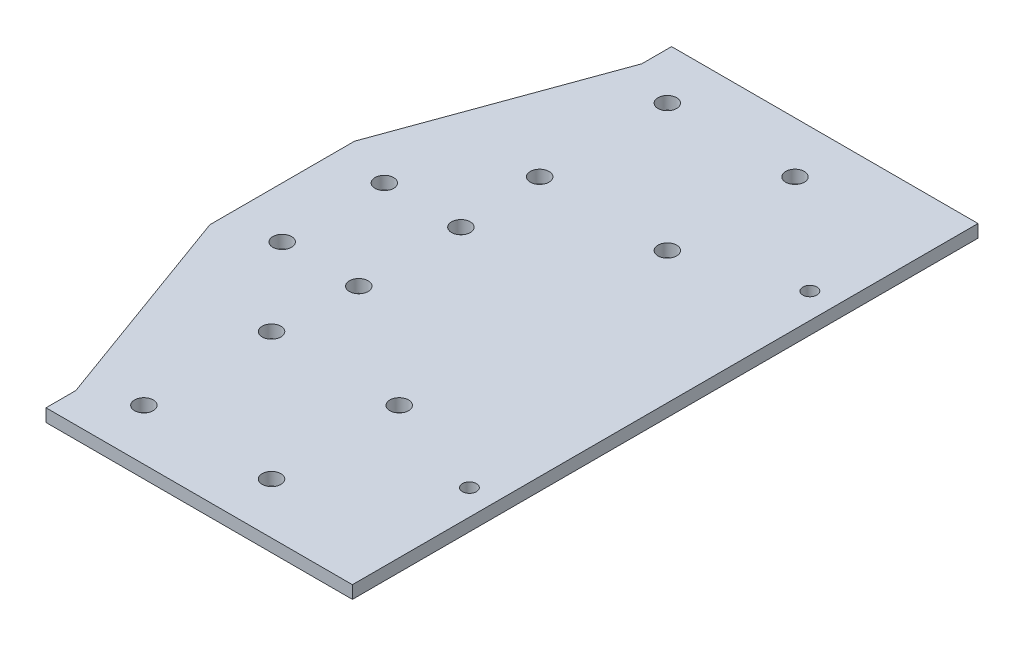
SolidWorks part; units mm, degrees
ref_plane "前视基准面" through (0, 0, 0) normal (0, 0, 1) x (1, 0, 0)
ref_plane "上视基准面" through (0, 0, 0) normal (0, 1, 0) x (1, 0, 0)
ref_plane "右视基准面" through (0, 0, 0) normal (1, 0, 0) x (0, 0, -1)
sketch "草图1" plane through (0, 0, 0) normal (0, 1, 0) x (1, 0, 0)
  line L1 (0, 0) -> (29.8465, 0)
  line L5 (-60.1535, 90.5) -> (-60.1535, 56.5)
  line L6 (-60.1535, 56.5) -> (-42.1535, 7)
  line L7 (-60.1535, 73.5) -> (-154.1656, 73.5) construction
  line L9 (-42.1535, 7) -> (-42.1535, 0)
  line L10 (-42.1535, 0) -> (0, 0)
  line L11 (29.8465, 0) -> (29.8465, 147)
  line L12 (0, 147) -> (29.8465, 147)
  line L13 (-42.1535, 147) -> (0, 147)
  line L14 (-42.1535, 140) -> (-42.1535, 147)
  line L15 (-60.1535, 90.5) -> (-42.1535, 140)
  dimension "D1" = 147
  dimension "D3" = 72
  dimension "D4" = 34
  dimension "D5" = 18
  dimension "D6" = 7
extrude "凸台-拉伸1" add sketch "草图1" along normal blind 3
sketch "草图2" plane through (0, 3, 0) normal (0, 1, 0) x (1, 0, 0)
  line L0 (-60.1535, 73.5) -> (80.4948, 73.5) construction
  line L1 (-60.1535, 90.5) -> (-60.1535, 56.5) construction
  line L3 (29.8465, 147) -> (-42.1535, 147) construction
  line L4 (-16.1535, 185.689) -> (-16.1535, 132.9913) construction
  line L5 (-42.1535, 147) -> (-42.1535, 140) construction
  line L6 (29.8465, 0) -> (29.8465, 147) construction
  circle A0 centre (-48.1535, 85.5) radius 2.2
  circle A1 centre (-30.1535, 85.5) radius 2.2
  circle A2 centre (-30.1535, 61.5) radius 2.2
  circle A3 centre (-48.1535, 61.5) radius 2.2
  circle A4 centre (-1.1535, 135) radius 2.2
  circle A5 centre (-1.1535, 105) radius 2.2
  circle A6 centre (-31.1535, 135) radius 2.2
  circle A7 centre (-31.1535, 105) radius 2.2
  circle A8 centre (-31.1535, 42) radius 2.2
  circle A9 centre (-31.1535, 12) radius 2.2
  circle A10 centre (-1.1535, 42) radius 2.2
  circle A11 centre (-1.1535, 12) radius 2.2
  circle A12 centre (23.8465, 113.5) radius 1.65
  circle A13 centre (23.8465, 33.5) radius 1.65
  dimension "D1" = 4.4
  dimension "D2" = 12
  dimension "D3" = 18
  dimension "D4" = 24
  dimension "D5" = 11
  dimension "D6" = 12
  dimension "D7" = 4.4
  dimension "D8" = 30
  dimension "D9" = 30
  dimension "D10" = 6
  dimension "D11" = 3.3
  dimension "D12" = 80
extrude "切除-拉伸1" cut sketch "草图2" against normal blind 10
